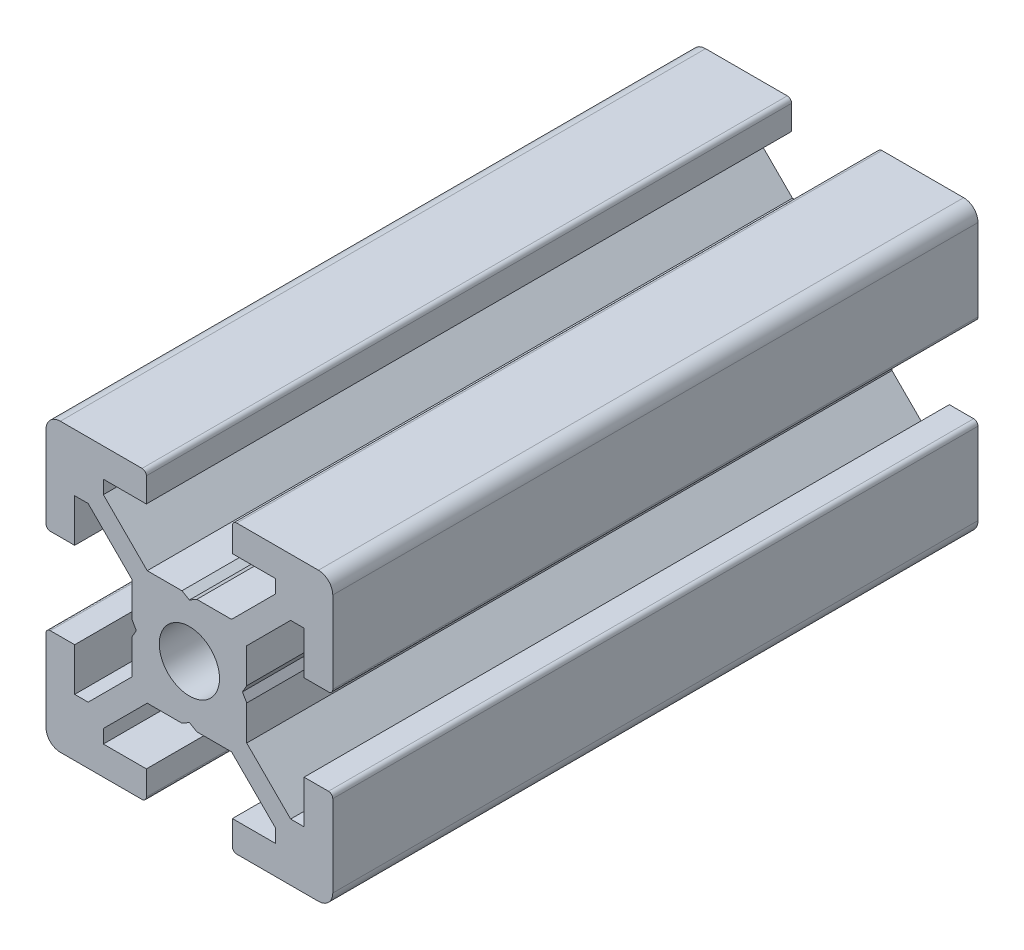
SolidWorks part; units mm, degrees
ref_plane "Front Plane" through (0, 0, 0) normal (0, 0, 1) x (1, 0, 0)
ref_plane "Top Plane" through (0, 0, 0) normal (0, 1, 0) x (1, 0, 0)
ref_plane "Right Plane" through (0, 0, 0) normal (1, 0, 0) x (0, 0, -1)
ref_plane "Plane1" through (0, 0, 0) normal (0, 0, 1) x (1, 0, 0)
sketch "Sketch1" plane through (0, 0, 0) normal (0, 0, 1) x (1, 0, 0)
  line L0 (-10, 9) -> (-10, 3.3)
  line L1 (-9.7, 3) -> (-8, 3)
  line L2 (-8, 3) -> (-8, 6)
  line L3 (-8, 6) -> (-7.0607, 6)
  line L4 (-7.0607, 6) -> (-4, 2.9393)
  line L5 (-4, 2.9393) -> (-4, 0.5196)
  line L6 (-4, 0.5196) -> (-3.7, 0)
  line L7 (-3.7, 0) -> (-4, -0.5196)
  line L8 (-4, -0.5196) -> (-4, -2.9393)
  line L9 (-4, -2.9393) -> (-7.0607, -6)
  line L10 (-7.0607, -6) -> (-8, -6)
  line L11 (-8, -6) -> (-8, -3)
  line L12 (-8, -3) -> (-9.7, -3)
  line L13 (-10, -3.3) -> (-10, -9)
  line L14 (-9, -10) -> (-3.3, -10)
  line L15 (-3, -9.7) -> (-3, -8)
  line L16 (-3, -8) -> (-6, -8)
  line L17 (-6, -8) -> (-6, -7.0607)
  line L18 (-6, -7.0607) -> (-2.9393, -4)
  line L19 (-2.9393, -4) -> (-0.5196, -4)
  line L20 (-0.5196, -4) -> (0, -3.7)
  line L21 (0, -3.7) -> (0.5196, -4)
  line L22 (0.5196, -4) -> (2.9393, -4)
  line L23 (2.9393, -4) -> (6, -7.0607)
  line L24 (6, -7.0607) -> (6, -8)
  line L25 (6, -8) -> (3, -8)
  line L26 (3, -8) -> (3, -9.7)
  line L27 (3.3, -10) -> (9, -10)
  line L28 (10, -9) -> (10, -3.3)
  line L29 (9.7, -3) -> (8, -3)
  line L30 (8, -3) -> (8, -6)
  line L31 (8, -6) -> (7.0606, -6)
  line L32 (7.0606, -6) -> (4, -2.9393)
  line L33 (4, -2.9393) -> (4, -0.5196)
  line L34 (4, -0.5196) -> (3.7, 0)
  line L35 (3.7, 0) -> (4, 0.5196)
  line L36 (4, 0.5196) -> (4, 2.9393)
  line L37 (4, 2.9393) -> (7.0607, 6)
  line L38 (7.0607, 6) -> (8, 6)
  line L39 (8, 6) -> (8, 3)
  line L40 (8, 3) -> (9.7, 3)
  line L41 (10, 3.3) -> (10, 9)
  line L42 (9, 10) -> (3.3, 10)
  line L43 (3, 9.7) -> (3, 8)
  line L44 (3, 8) -> (6, 8)
  line L45 (6, 8) -> (6, 7.0607)
  line L46 (6, 7.0607) -> (2.9393, 4)
  line L47 (2.9393, 4) -> (0.5196, 4)
  line L48 (0.5196, 4) -> (0, 3.7)
  line L49 (0, 3.7) -> (-0.5196, 4)
  line L50 (-0.5196, 4) -> (-2.9394, 4)
  line L51 (-2.9394, 4) -> (-6, 7.0606)
  line L52 (-6, 7.0606) -> (-6, 8)
  line L53 (-6, 8) -> (-3, 8)
  line L54 (-3, 8) -> (-3, 9.7)
  line L55 (-3.3, 10) -> (-9, 10)
  arc A0 (-10, 3.3) -> (-9.7, 3) centre (-9.7, 3.3) ccw
  arc A1 (-9.7, -3) -> (-10, -3.3) centre (-9.7, -3.3) ccw
  arc A2 (-10, -9) -> (-9, -10) centre (-9, -9) ccw
  arc A3 (-3.3, -10) -> (-3, -9.7) centre (-3.3, -9.7) ccw
  arc A4 (3, -9.7) -> (3.3, -10) centre (3.3, -9.7) ccw
  arc A5 (9, -10) -> (10, -9) centre (9, -9) ccw
  arc A6 (10, -3.3) -> (9.7, -3) centre (9.7, -3.3) ccw
  arc A7 (9.7, 3) -> (10, 3.3) centre (9.7, 3.3) ccw
  arc A8 (10, 9) -> (9, 10) centre (9, 9) ccw
  arc A9 (3.3, 10) -> (3, 9.7) centre (3.3, 9.7) ccw
  arc A10 (-3, 9.7) -> (-3.3, 10) centre (-3.3, 9.7) ccw
  arc A11 (-9, 10) -> (-10, 9) centre (-9, 9) ccw
extrude "Boss-Extrude1" add sketch "Sketch1" against normal blind 45
ref_plane "Plane2" through (0, 0, 0) normal (1, 0, 0) x (0, 0, -1)
sketch "Sketch2" plane through (0, 0, 0) normal (1, 0, 0) x (0, 0, -1)
  line L0 (0, 0) -> (0, 2.1)
  line L1 (0, 2.1) -> (400, 2.1)
  line L2 (400, 2.1) -> (400, 0)
  line L3 (400, 0) -> (0, 0)
  line L4 (400, 0) -> (0, 0) construction
revolve "Cut-Revolve1" cut sketch "Sketch2" angle 360 about L4
